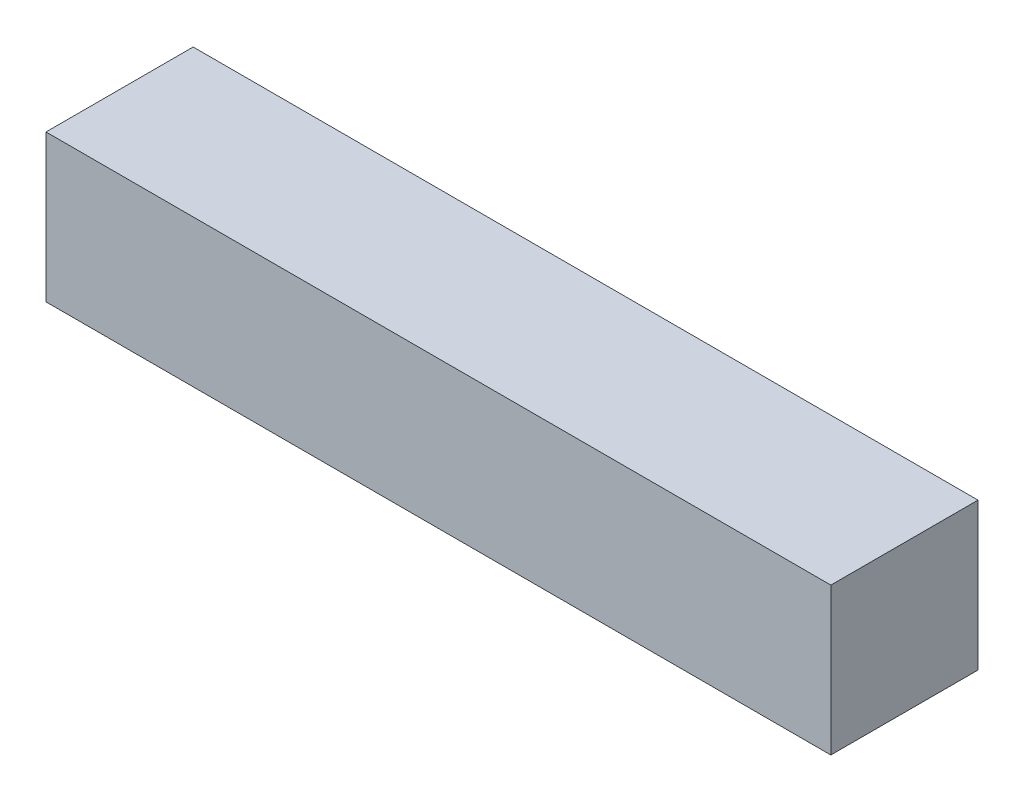
SolidWorks part; units mm, degrees
material "Pine"
ref_plane "Front Plane" through (0, 0, 0) normal (0, 0, 1) x (1, 0, 0)
ref_plane "Top Plane" through (0, 0, 0) normal (0, 1, 0) x (1, 0, 0)
ref_plane "Right Plane" through (0, 0, 0) normal (1, 0, 0) x (0, 0, -1)
sketch "Sketch1" plane through (0, 0, 0) normal (0, 0, 1) x (1, 0, 0)
  line L1 (-101.6, 19.05) -> (101.6, 19.05)
  line L2 (-101.6, 19.05) -> (-101.6, -19.05)
  line L3 (-101.6, -19.05) -> (101.6, -19.05)
  line L4 (101.6, 19.05) -> (101.6, -19.05)
  point P4 (0, 19.05)
  point P6 (101.6, 0)
  dimension "D1" = 203.2
  dimension "D2" = 38.1
extrude "Boss-Extrude1" add sketch "Sketch1" along normal blind 38.1
